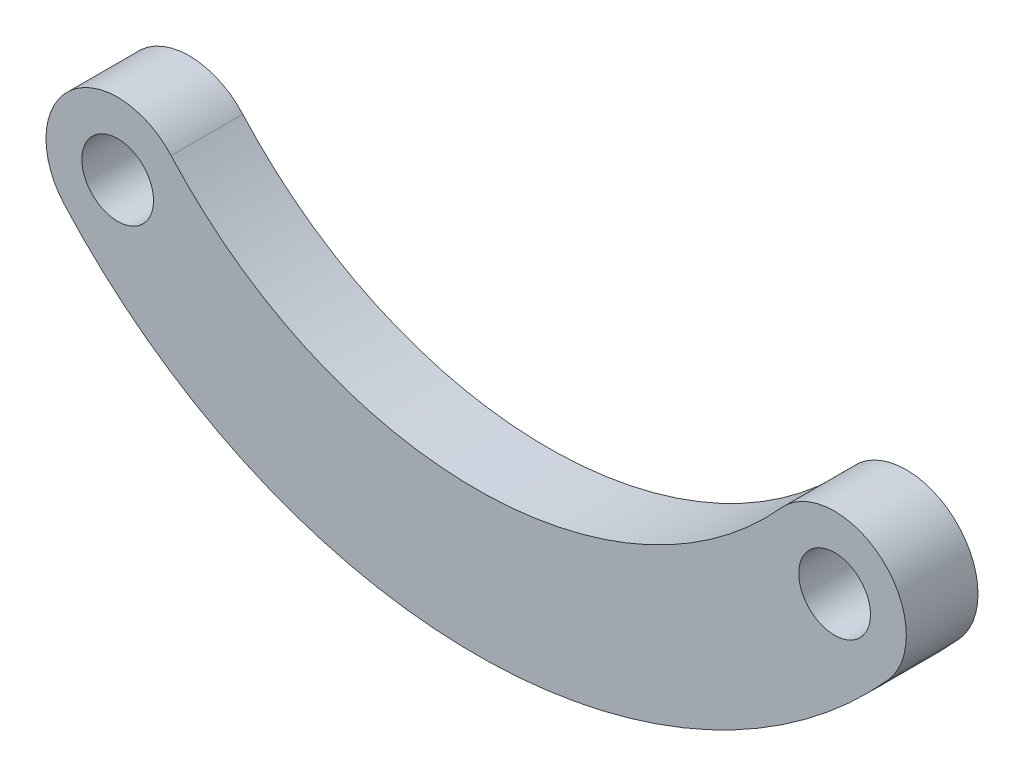
SolidWorks part; units mm, degrees
ref_plane "Front Plane" through (0, 0, 0) normal (0, 0, 1) x (1, 0, 0)
ref_plane "Top Plane" through (0, 0, 0) normal (0, 1, 0) x (1, 0, 0)
ref_plane "Right Plane" through (0, 0, 0) normal (1, 0, 0) x (0, 0, -1)
sketch "Sketch1" plane through (0, 0, 0) normal (0, 0, 1) x (1, 0, 0)
  line L0 (-95.25, -85.2942) -> (-81.0584, -72.586) construction
  line L1 (-81.0584, -72.586) -> (-109.4416, -98.0025) construction
  arc A0 (81.0584, -72.586) -> (109.4416, -98.0025) centre (95.25, -85.2942) cw
  circle A1 centre (-95.25, -85.2942) radius 9.525
  arc A2 (109.4416, -98.0025) -> (-109.4416, -98.0025) centre (0, 0) cw
  arc A3 (81.0584, -72.586) -> (-81.0584, -72.586) centre (0, 0) cw
  arc A4 (-81.0584, -72.586) -> (-109.4416, -98.0025) centre (-95.25, -85.2942) ccw
  circle A5 centre (95.25, -85.2942) radius 9.525
  dimension "D1" = 38.1
  dimension "D2" = 19.05
  dimension "D3" = 190.5
extrude "Boss-Extrude1" add sketch "Sketch1" along normal blind 19.05
